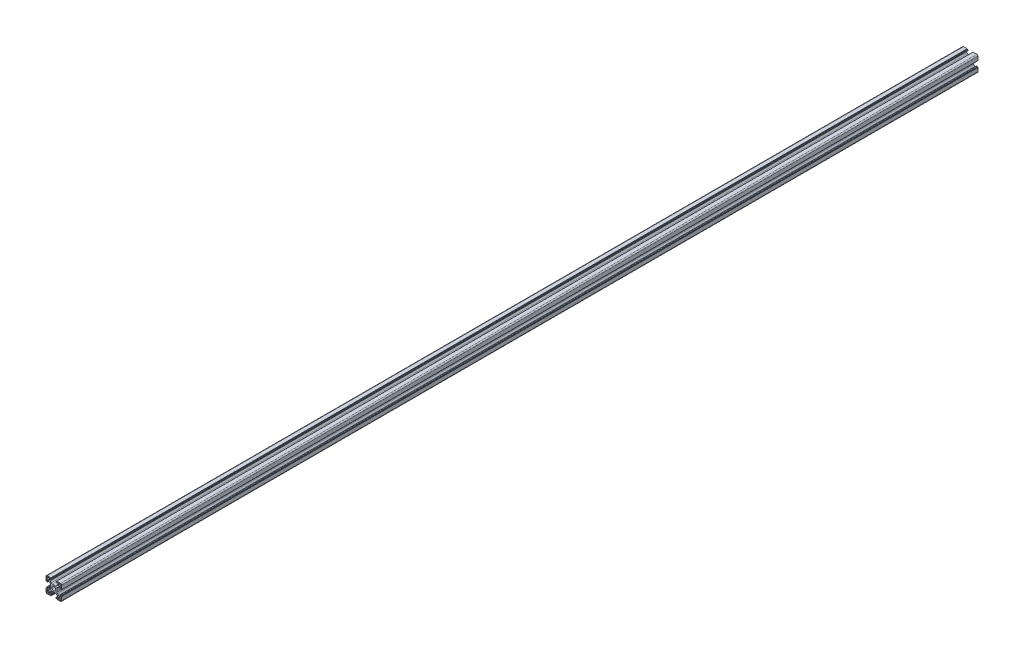
SolidWorks part; units mm, degrees
material "1060 Сплав"
ref_plane "Спереди" through (0, 0, 0) normal (0, 0, 1) x (1, 0, 0)
ref_plane "Сверху" through (0, 0, 0) normal (0, 1, 0) x (1, 0, 0)
ref_plane "Справа" through (0, 0, 0) normal (1, 0, 0) x (0, 0, -1)
sketch "Эскиз1" plane through (0, 0, 0) normal (0, 0, 1) x (1, 0, 0)
  line L0 (-22.0052, 70.3096) -> (-25.0052, 67.3096) construction
  line L1 (-31.1052, 65.2096) -> (-29.2064, 65.2096)
  line L2 (-31.1052, 61.2096) -> (-21.1052, 71.2096) construction
  line L3 (-23.5052, 68.8096) -> (-25.0052, 70.3096) construction
  line L4 (-27.7922, 65.7954) -> (-26.4909, 67.0967)
  line L5 (-24.2052, 67.3096) -> (-22.8052, 67.3096)
  line L6 (-25.0052, 68.1096) -> (-25.0052, 69.5096)
  line L7 (-22.8052, 70.3096) -> (-24.2052, 70.3096)
  line L8 (-25.9052, 69.4096) -> (-25.9052, 68.5109)
  line L9 (-27.3419, 69.2829) -> (-26.8616, 69.7632)
  line L10 (-27.9052, 70.7587) -> (-27.4052, 70.7587)
  line L11 (-27.5187, 69.2096) -> (-27.8052, 69.2096)
  line L12 (-26.508, 69.9096) -> (-26.4052, 69.9096)
  line L13 (-27.4052, 71.0596) -> (-27.4052, 70.7587)
  line L14 (-28.0552, 70.6087) -> (-28.0552, 69.4596)
  line L15 (-22.6052, 71.2096) -> (-27.2552, 71.2096)
  line L16 (-22.0052, 69.5096) -> (-22.0052, 68.1096)
  line L17 (-21.1052, 69.7096) -> (-21.1052, 65.0596)
  line L18 (-21.7061, 64.2596) -> (-22.8552, 64.2596)
  line L19 (-21.2552, 64.9096) -> (-21.5561, 64.9096)
  line L20 (-22.4052, 65.8068) -> (-22.4052, 65.9096)
  line L21 (-23.1052, 64.7961) -> (-23.1052, 64.5096)
  line L22 (-21.5561, 64.4096) -> (-21.5561, 64.9096)
  line L23 (-23.0319, 64.9729) -> (-22.5516, 65.4532)
  line L24 (-22.9052, 66.4096) -> (-23.8039, 66.4096)
  line L25 (-26.5194, 64.5226) -> (-25.2181, 65.8239)
  line L26 (-27.1052, 61.2096) -> (-27.1052, 63.1084)
  line L27 (-27.1052, 61.2096) -> (-27.1052, 59.3109)
  line L28 (-26.5194, 57.8967) -> (-25.2181, 56.5954)
  line L29 (-25.0052, 54.3096) -> (-25.0052, 52.9096)
  line L30 (-24.2052, 55.1096) -> (-22.8052, 55.1096)
  line L31 (-22.0052, 52.9096) -> (-22.0052, 54.3096)
  line L32 (-22.9052, 56.0096) -> (-23.8039, 56.0096)
  line L33 (-23.0319, 57.4464) -> (-22.5516, 56.9661)
  line L34 (-21.5561, 58.0096) -> (-21.5561, 57.5096)
  line L35 (-23.1052, 57.6232) -> (-23.1052, 57.9096)
  line L36 (-22.4052, 56.6125) -> (-22.4052, 56.5096)
  line L37 (-21.2552, 57.5096) -> (-21.5561, 57.5096)
  line L38 (-21.7061, 58.1596) -> (-22.8552, 58.1596)
  line L39 (-21.1052, 52.7096) -> (-21.1052, 57.3596)
  line L40 (-22.8052, 52.1096) -> (-24.2052, 52.1096)
  line L41 (-22.6052, 51.2096) -> (-27.2552, 51.2096)
  line L42 (-28.0552, 51.8106) -> (-28.0552, 52.9596)
  line L43 (-27.4052, 51.3596) -> (-27.4052, 51.6606)
  line L44 (-26.508, 52.5096) -> (-26.4052, 52.5096)
  line L45 (-27.5187, 53.2096) -> (-27.8052, 53.2096)
  line L46 (-27.9052, 51.6606) -> (-27.4052, 51.6606)
  line L47 (-27.3419, 53.1364) -> (-26.8616, 52.6561)
  line L48 (-25.9052, 53.0096) -> (-25.9052, 53.9084)
  line L49 (-27.7922, 56.6239) -> (-26.4909, 55.3226)
  line L50 (-31.1052, 57.2096) -> (-29.2064, 57.2096)
  line L51 (-22.0052, 52.1096) -> (-25.0052, 55.1096) construction
  line L52 (-31.1052, 61.2096) -> (-21.1052, 51.2096) construction
  line L53 (-23.5052, 53.6096) -> (-22.0052, 55.1096) construction
  line L54 (-31.1052, 57.2096) -> (-33.0039, 57.2096)
  line L55 (-34.4181, 56.6239) -> (-35.7194, 55.3226)
  line L56 (-38.0052, 55.1096) -> (-39.4052, 55.1096)
  line L57 (-37.2052, 54.3096) -> (-37.2052, 52.9096)
  line L58 (-39.4052, 52.1096) -> (-38.0052, 52.1096)
  line L59 (-36.3052, 53.0096) -> (-36.3052, 53.9084)
  line L60 (-34.8684, 53.1364) -> (-35.3487, 52.6561)
  line L61 (-34.3052, 51.6606) -> (-34.8052, 51.6606)
  line L62 (-34.6916, 53.2096) -> (-34.4052, 53.2096)
  line L63 (-35.7023, 52.5096) -> (-35.8052, 52.5096)
  line L64 (-34.8052, 51.3596) -> (-34.8052, 51.6606)
  line L65 (-34.1552, 51.8106) -> (-34.1552, 52.9596)
  line L66 (-39.6052, 51.2096) -> (-34.9552, 51.2096)
  line L67 (-40.2052, 52.9096) -> (-40.2052, 54.3096)
  line L68 (-41.1052, 52.7096) -> (-41.1052, 57.3596)
  line L69 (-40.5042, 58.1596) -> (-39.3552, 58.1596)
  line L70 (-40.9552, 57.5096) -> (-40.6542, 57.5096)
  line L71 (-39.8052, 56.6125) -> (-39.8052, 56.5096)
  line L72 (-39.1052, 57.6232) -> (-39.1052, 57.9096)
  line L73 (-40.6542, 58.0096) -> (-40.6542, 57.5096)
  line L74 (-39.1784, 57.4464) -> (-39.6587, 56.9661)
  line L75 (-39.3052, 56.0096) -> (-38.4064, 56.0096)
  line L76 (-35.6909, 57.8967) -> (-36.9922, 56.5954)
  line L77 (-35.1052, 61.2096) -> (-35.1052, 59.3109)
  line L78 (-40.2052, 52.1096) -> (-37.2052, 55.1096) construction
  line L79 (-31.1052, 61.2096) -> (-41.1052, 51.2096) construction
  line L80 (-38.7052, 53.6096) -> (-37.2052, 52.1096) construction
  line L81 (-35.1052, 61.2096) -> (-35.1052, 63.1084)
  line L82 (-35.6909, 64.5226) -> (-36.9922, 65.8239)
  line L83 (-37.2052, 68.1096) -> (-37.2052, 69.5096)
  line L84 (-38.0052, 67.3096) -> (-39.4052, 67.3096)
  line L85 (-40.2052, 69.5096) -> (-40.2052, 68.1096)
  line L86 (-39.3052, 66.4096) -> (-38.4064, 66.4096)
  line L87 (-39.1784, 64.9729) -> (-39.6587, 65.4532)
  line L88 (-40.6542, 64.4096) -> (-40.6542, 64.9096)
  line L89 (-39.1052, 64.7961) -> (-39.1052, 64.5096)
  line L90 (-39.8052, 65.8068) -> (-39.8052, 65.9096)
  line L91 (-40.9552, 64.9096) -> (-40.6542, 64.9096)
  line L92 (-40.5042, 64.2596) -> (-39.3552, 64.2596)
  line L93 (-41.1052, 69.7096) -> (-41.1052, 65.0596)
  line L94 (-39.4052, 70.3096) -> (-38.0052, 70.3096)
  line L95 (-39.6052, 71.2096) -> (-34.9552, 71.2096)
  line L96 (-34.1552, 70.6087) -> (-34.1552, 69.4596)
  line L97 (-34.8052, 71.0596) -> (-34.8052, 70.7587)
  line L98 (-35.7023, 69.9096) -> (-35.8052, 69.9096)
  line L99 (-34.6916, 69.2096) -> (-34.4052, 69.2096)
  line L100 (-34.3052, 70.7587) -> (-34.8052, 70.7587)
  line L101 (-34.8684, 69.2829) -> (-35.3487, 69.7632)
  line L102 (-36.3052, 69.4096) -> (-36.3052, 68.5109)
  line L103 (-34.4181, 65.7954) -> (-35.7194, 67.0967)
  line L104 (-31.1052, 65.2096) -> (-33.0039, 65.2096)
  line L105 (-42.8692, 61.2096) -> (-19.6008, 61.2096) construction
  line L106 (-40.2052, 70.3096) -> (-37.2052, 67.3096) construction
  line L107 (-31.1052, 49.1232) -> (-31.1052, 71.9286) construction
  line L108 (-31.1052, 61.2096) -> (-41.1052, 71.2096) construction
  line L109 (-38.7052, 68.8096) -> (-40.2052, 67.3096) construction
  arc A0 (-22.0052, 69.5096) -> (-22.8052, 70.3096) centre (-22.8052, 69.5096) ccw
  arc A1 (-24.2052, 70.3096) -> (-25.0052, 69.5096) centre (-24.2052, 69.5096) ccw
  arc A2 (-24.2052, 67.3096) -> (-25.0052, 68.1096) centre (-24.2052, 68.1096) cw
  arc A3 (-22.6052, 71.2096) -> (-21.1052, 69.7096) centre (-22.6052, 69.7096) cw
  arc A4 (-27.9052, 70.7587) -> (-28.0552, 70.6087) centre (-27.9052, 70.6087) ccw
  arc A5 (-27.2552, 71.2096) -> (-27.4052, 71.0596) centre (-27.2552, 71.0596) ccw
  arc A6 (-27.5187, 69.2096) -> (-27.3419, 69.2829) centre (-27.5187, 69.4596) ccw
  arc A7 (-27.8052, 69.2096) -> (-28.0552, 69.4596) centre (-27.8052, 69.4596) cw
  arc A8 (-26.8616, 69.7632) -> (-26.508, 69.9096) centre (-26.508, 69.4096) cw
  arc A9 (-26.4052, 69.9096) -> (-25.9052, 69.4096) centre (-26.4052, 69.4096) cw
  arc A10 (-28.6052, 61.2096) -> (-31.1052, 63.7096) centre (-31.1052, 61.2096) ccw
  arc A11 (-29.2064, 65.2096) -> (-27.7922, 65.7954) centre (-29.2064, 67.2096) ccw
  arc A12 (-25.9052, 68.5109) -> (-26.4909, 67.0967) centre (-27.9052, 68.5109) cw
  arc A13 (-22.0052, 68.1096) -> (-22.8052, 67.3096) centre (-22.8052, 68.1096) cw
  arc A14 (-22.4052, 65.9096) -> (-22.9052, 66.4096) centre (-22.9052, 65.9096) ccw
  arc A15 (-22.5516, 65.4532) -> (-22.4052, 65.8068) centre (-22.9052, 65.8068) ccw
  arc A16 (-23.1052, 64.5096) -> (-22.8552, 64.2596) centre (-22.8552, 64.5096) ccw
  arc A17 (-23.1052, 64.7961) -> (-23.0319, 64.9729) centre (-22.8552, 64.7961) cw
  arc A18 (-21.1052, 65.0596) -> (-21.2552, 64.9096) centre (-21.2552, 65.0596) cw
  arc A19 (-21.5561, 64.4096) -> (-21.7061, 64.2596) centre (-21.7061, 64.4096) cw
  arc A20 (-23.8039, 66.4096) -> (-25.2181, 65.8239) centre (-23.8039, 64.4096) ccw
  arc A21 (-27.1052, 63.1084) -> (-26.5194, 64.5226) centre (-25.1052, 63.1084) cw
  arc A22 (-22.8052, 52.1096) -> (-22.0052, 52.9096) centre (-22.8052, 52.9096) ccw
  arc A23 (-22.0052, 54.3096) -> (-22.8052, 55.1096) centre (-22.8052, 54.3096) ccw
  arc A24 (-25.0052, 54.3096) -> (-24.2052, 55.1096) centre (-24.2052, 54.3096) cw
  arc A25 (-21.1052, 52.7096) -> (-22.6052, 51.2096) centre (-22.6052, 52.7096) cw
  arc A26 (-21.5561, 58.0096) -> (-21.7061, 58.1596) centre (-21.7061, 58.0096) ccw
  arc A27 (-21.1052, 57.3596) -> (-21.2552, 57.5096) centre (-21.2552, 57.3596) ccw
  arc A28 (-23.1052, 57.6232) -> (-23.0319, 57.4464) centre (-22.8552, 57.6232) ccw
  arc A29 (-23.1052, 57.9096) -> (-22.8552, 58.1596) centre (-22.8552, 57.9096) cw
  arc A30 (-22.5516, 56.9661) -> (-22.4052, 56.6125) centre (-22.9052, 56.6125) cw
  arc A31 (-22.4052, 56.5096) -> (-22.9052, 56.0096) centre (-22.9052, 56.5096) cw
  arc A32 (-31.1052, 58.7096) -> (-28.6052, 61.2096) centre (-31.1052, 61.2096) ccw
  arc A33 (-27.1052, 59.3109) -> (-26.5194, 57.8967) centre (-25.1052, 59.3109) ccw
  arc A34 (-23.8039, 56.0096) -> (-25.2181, 56.5954) centre (-23.8039, 58.0096) cw
  arc A35 (-24.2052, 52.1096) -> (-25.0052, 52.9096) centre (-24.2052, 52.9096) cw
  arc A36 (-26.4052, 52.5096) -> (-25.9052, 53.0096) centre (-26.4052, 53.0096) ccw
  arc A37 (-26.8616, 52.6561) -> (-26.508, 52.5096) centre (-26.508, 53.0096) ccw
  arc A38 (-27.8052, 53.2096) -> (-28.0552, 52.9596) centre (-27.8052, 52.9596) ccw
  arc A39 (-27.5187, 53.2096) -> (-27.3419, 53.1364) centre (-27.5187, 52.9596) cw
  arc A40 (-27.2552, 51.2096) -> (-27.4052, 51.3596) centre (-27.2552, 51.3596) cw
  arc A41 (-27.9052, 51.6606) -> (-28.0552, 51.8106) centre (-27.9052, 51.8106) cw
  arc A42 (-25.9052, 53.9084) -> (-26.4909, 55.3226) centre (-27.9052, 53.9084) ccw
  arc A43 (-29.2064, 57.2096) -> (-27.7922, 56.6239) centre (-29.2064, 55.2096) cw
  arc A44 (-40.2052, 52.9096) -> (-39.4052, 52.1096) centre (-39.4052, 52.9096) ccw
  arc A45 (-38.0052, 52.1096) -> (-37.2052, 52.9096) centre (-38.0052, 52.9096) ccw
  arc A46 (-38.0052, 55.1096) -> (-37.2052, 54.3096) centre (-38.0052, 54.3096) cw
  arc A47 (-39.6052, 51.2096) -> (-41.1052, 52.7096) centre (-39.6052, 52.7096) cw
  arc A48 (-34.3052, 51.6606) -> (-34.1552, 51.8106) centre (-34.3052, 51.8106) ccw
  arc A49 (-34.9552, 51.2096) -> (-34.8052, 51.3596) centre (-34.9552, 51.3596) ccw
  arc A50 (-34.6916, 53.2096) -> (-34.8684, 53.1364) centre (-34.6916, 52.9596) ccw
  arc A51 (-34.4052, 53.2096) -> (-34.1552, 52.9596) centre (-34.4052, 52.9596) cw
  arc A52 (-35.3487, 52.6561) -> (-35.7023, 52.5096) centre (-35.7023, 53.0096) cw
  arc A53 (-35.8052, 52.5096) -> (-36.3052, 53.0096) centre (-35.8052, 53.0096) cw
  arc A54 (-33.6052, 61.2096) -> (-31.1052, 58.7096) centre (-31.1052, 61.2096) ccw
  arc A55 (-33.0039, 57.2096) -> (-34.4181, 56.6239) centre (-33.0039, 55.2096) ccw
  arc A56 (-36.3052, 53.9084) -> (-35.7194, 55.3226) centre (-34.3052, 53.9084) cw
  arc A57 (-40.2052, 54.3096) -> (-39.4052, 55.1096) centre (-39.4052, 54.3096) cw
  arc A58 (-39.8052, 56.5096) -> (-39.3052, 56.0096) centre (-39.3052, 56.5096) ccw
  arc A59 (-39.6587, 56.9661) -> (-39.8052, 56.6125) centre (-39.3052, 56.6125) ccw
  arc A60 (-39.1052, 57.9096) -> (-39.3552, 58.1596) centre (-39.3552, 57.9096) ccw
  arc A61 (-39.1052, 57.6232) -> (-39.1784, 57.4464) centre (-39.3552, 57.6232) cw
  arc A62 (-41.1052, 57.3596) -> (-40.9552, 57.5096) centre (-40.9552, 57.3596) cw
  arc A63 (-40.6542, 58.0096) -> (-40.5042, 58.1596) centre (-40.5042, 58.0096) cw
  arc A64 (-38.4064, 56.0096) -> (-36.9922, 56.5954) centre (-38.4064, 58.0096) ccw
  arc A65 (-35.1052, 59.3109) -> (-35.6909, 57.8967) centre (-37.1052, 59.3109) cw
  arc A66 (-39.4052, 70.3096) -> (-40.2052, 69.5096) centre (-39.4052, 69.5096) ccw
  arc A67 (-40.2052, 68.1096) -> (-39.4052, 67.3096) centre (-39.4052, 68.1096) ccw
  arc A68 (-37.2052, 68.1096) -> (-38.0052, 67.3096) centre (-38.0052, 68.1096) cw
  arc A69 (-41.1052, 69.7096) -> (-39.6052, 71.2096) centre (-39.6052, 69.7096) cw
  arc A70 (-40.6542, 64.4096) -> (-40.5042, 64.2596) centre (-40.5042, 64.4096) ccw
  arc A71 (-41.1052, 65.0596) -> (-40.9552, 64.9096) centre (-40.9552, 65.0596) ccw
  arc A72 (-39.1052, 64.7961) -> (-39.1784, 64.9729) centre (-39.3552, 64.7961) ccw
  arc A73 (-39.1052, 64.5096) -> (-39.3552, 64.2596) centre (-39.3552, 64.5096) cw
  arc A74 (-39.6587, 65.4532) -> (-39.8052, 65.8068) centre (-39.3052, 65.8068) cw
  arc A75 (-39.8052, 65.9096) -> (-39.3052, 66.4096) centre (-39.3052, 65.9096) cw
  arc A76 (-31.1052, 63.7096) -> (-33.6052, 61.2096) centre (-31.1052, 61.2096) ccw
  arc A77 (-35.1052, 63.1084) -> (-35.6909, 64.5226) centre (-37.1052, 63.1084) ccw
  arc A78 (-38.4064, 66.4096) -> (-36.9922, 65.8239) centre (-38.4064, 64.4096) cw
  arc A79 (-38.0052, 70.3096) -> (-37.2052, 69.5096) centre (-38.0052, 69.5096) cw
  arc A80 (-35.8052, 69.9096) -> (-36.3052, 69.4096) centre (-35.8052, 69.4096) ccw
  arc A81 (-35.3487, 69.7632) -> (-35.7023, 69.9096) centre (-35.7023, 69.4096) ccw
  arc A82 (-34.4052, 69.2096) -> (-34.1552, 69.4596) centre (-34.4052, 69.4596) ccw
  arc A83 (-34.6916, 69.2096) -> (-34.8684, 69.2829) centre (-34.6916, 69.4596) cw
  arc A84 (-34.9552, 71.2096) -> (-34.8052, 71.0596) centre (-34.9552, 71.0596) cw
  arc A85 (-34.3052, 70.7587) -> (-34.1552, 70.6087) centre (-34.3052, 70.6087) cw
  arc A86 (-36.3052, 68.5109) -> (-35.7194, 67.0967) centre (-34.3052, 68.5109) ccw
  arc A87 (-33.0039, 65.2096) -> (-34.4181, 65.7954) centre (-33.0039, 67.2096) cw
  point P0 (-31.1052, 61.2096)
  point P9 (-31.1052, 61.2096)
  point P40 (-22.4052, 64.9096)
  point P93 (-27.4052, 52.5096)
  point P144 (-27.4052, 69.9096)
  point P152 (-22.4052, 57.5096)
  point P153 (-31.1052, 57.2854)
  point P154 (-31.1052, 61.2096)
  point P189 (-39.8052, 57.5096)
  point P228 (-34.8052, 52.5096)
  point P229 (-35.0294, 61.2096)
  point P230 (-31.1052, 61.2096)
  point P268 (-34.8052, 69.9096)
  point P273 (-27.1809, 61.2096)
  point P306 (-39.8052, 64.9096)
  point P307 (-31.1052, 65.1339)
  point P309 (-31.1052, 61.2096)
  dimension "D3" = 5
  dimension "D6" = 2
  dimension "D1" = 2
  dimension "D2" = 6
  dimension "D4" = 4
  dimension "D5" = 0.9
extrude "Бобышка-Вытянуть1" add sketch "Эскиз1" along normal blind 1175
